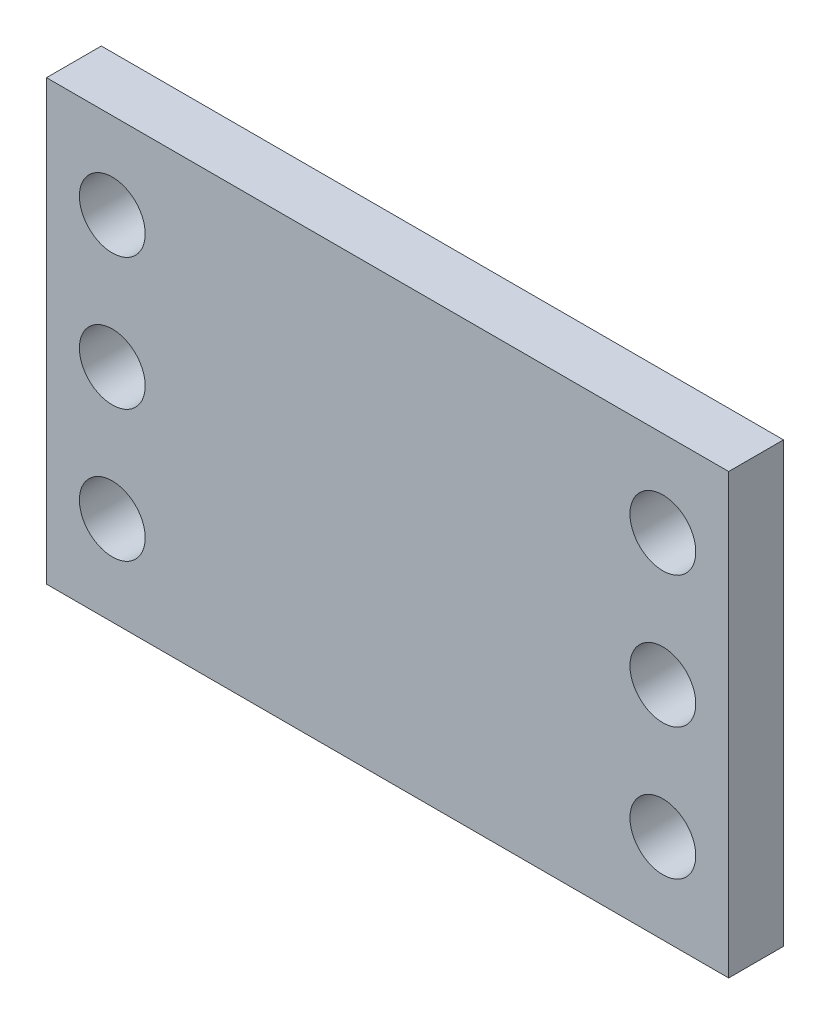
SolidWorks part; units mm, degrees
material "Bronce de aluminio"
ref_plane "Alzado" through (0, 0, 0) normal (0, 0, 1) x (1, 0, 0)
ref_plane "Planta" through (0, 0, 0) normal (0, 1, 0) x (1, 0, 0)
ref_plane "Vista lateral" through (0, 0, 0) normal (1, 0, 0) x (0, 0, -1)
sketch "Croquis1" plane through (0, 0, 0) normal (0, 0, 1) x (1, 0, 0)
  line L1 (37.9751, 19.24) -> (100.1815, 19.24)
  line L2 (37.9751, 19.24) -> (37.9751, 59.24)
  line L3 (37.9751, 59.24) -> (100.1815, 59.24)
  line L4 (100.1815, 19.24) -> (100.1815, 59.24)
  line L5 (37.9751, 59.24) -> (37.9751, 19.24) construction
extrude "Saliente-Extruir1" add sketch "Croquis1" along normal blind 5
sketch "Croquis9" plane through (0, 0, 0) normal (0, 0, -1) x (-1, 0, 0)
  circle A0 centre (-94.1815, 27.3944) radius 3
  circle A1 centre (-94.1815, 39.3944) radius 3
  circle A2 centre (-94.1815, 51.3944) radius 3
  circle A3 centre (-43.9751, 27.3944) radius 3
  circle A4 centre (-43.9751, 39.3944) radius 3
  circle A5 centre (-43.9751, 51.3944) radius 3
extrude "Cortar-Extruir2" cut sketch "Croquis9" against normal blind 10
